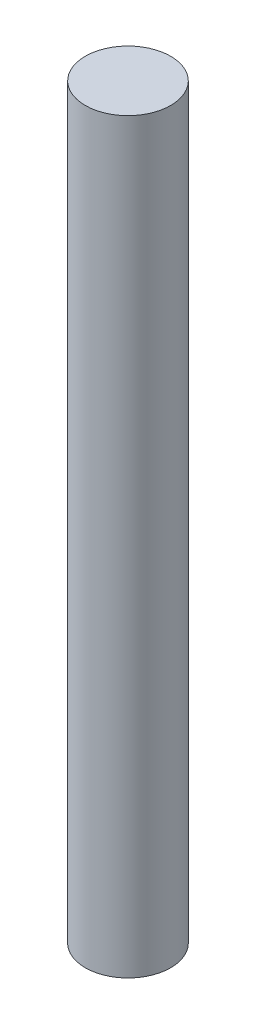
SolidWorks part; units mm, degrees
material "AISI 304"
ref_plane "Front Plane" through (0, 0, 0) normal (0, 0, 1) x (1, 0, 0)
ref_plane "Top Plane" through (0, 0, 0) normal (0, 1, 0) x (1, 0, 0)
ref_plane "Right Plane" through (0, 0, 0) normal (1, 0, 0) x (0, 0, -1)
sketch "Sketch1" plane through (0, 0, 0) normal (0, 1, 0) x (1, 0, 0)
  circle A0 centre (0, 0) radius 1
  dimension "D1" = 2
extrude "Boss-Extrude1" add sketch "Sketch1" along normal blind 17.5
